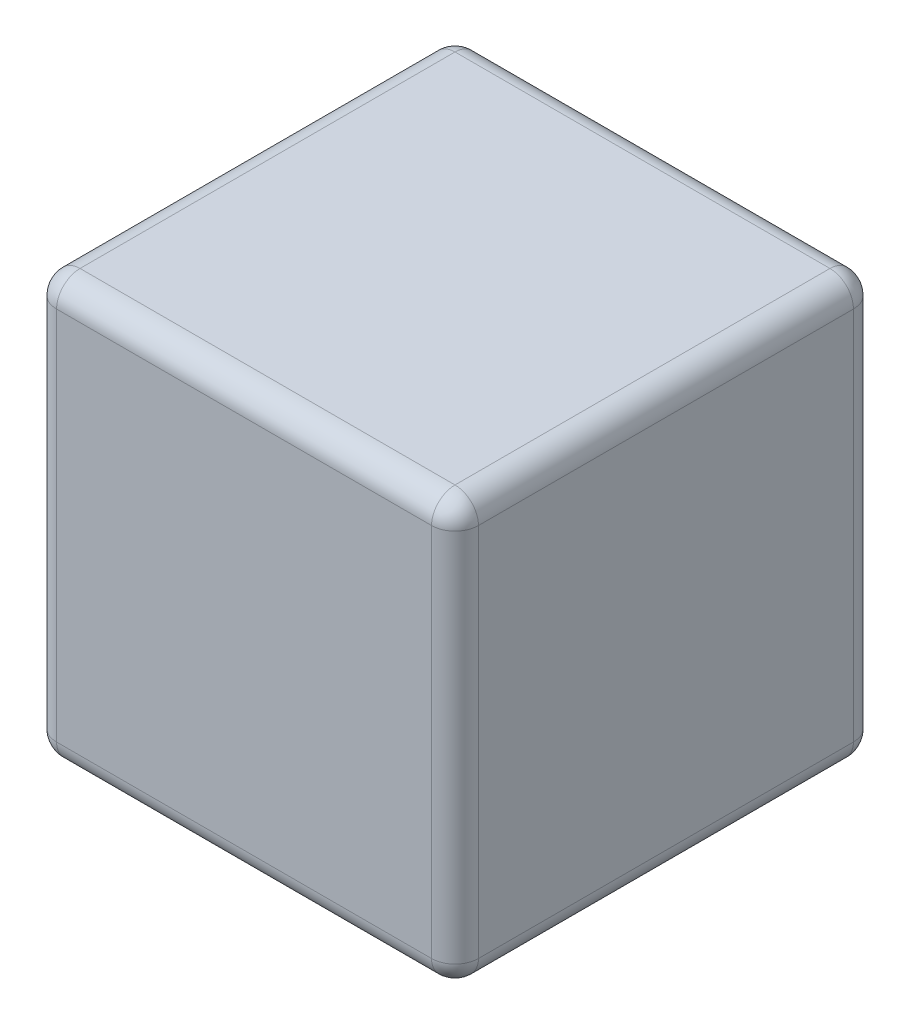
SolidWorks part; units mm, degrees
ref_plane "前视基准面" through (0, 0, 0) normal (0, 0, 1) x (1, 0, 0)
ref_plane "上视基准面" through (0, 0, 0) normal (0, 1, 0) x (1, 0, 0)
ref_plane "右视基准面" through (0, 0, 0) normal (1, 0, 0) x (0, 0, -1)
sketch "草图1" plane through (0, 0, 0) normal (0, 1, 0) x (1, 0, 0)
  line L1 (0, 0) -> (18, 0)
  line L2 (0, 0) -> (0, 18)
  line L3 (0, 18) -> (18, 18)
  line L4 (18, 0) -> (18, 18)
  dimension "D1" = 18
  dimension "D2" = 18
extrude "凸台-拉伸1" add sketch "草图1" along normal blind 18
fillet "圆角1" radius 1 12 edges at (9, 0, -18) (18, 9, -18) (18, 0, -9) (9, 18, -18) (18, 18, -9) (0, 9, -18) (0, 18, -9) (0, 0, -9) (0, 9, 0) (9, 18, 0) (18, 9, 0) (9, 0, 0)
